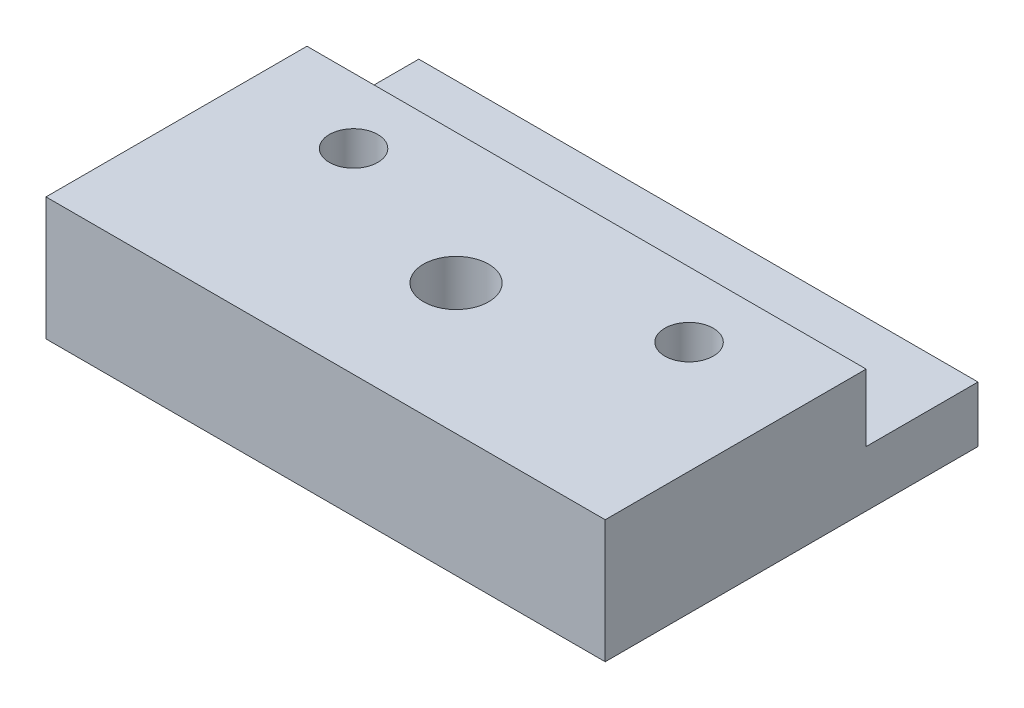
SolidWorks part; units mm, degrees
ref_plane "前基準面" through (0, 0, 0) normal (0, 0, 1) x (1, 0, 0)
ref_plane "上基準面" through (0, 0, 0) normal (0, 1, 0) x (1, 0, 0)
ref_plane "右基準面" through (0, 0, 0) normal (1, 0, 0) x (0, 0, -1)
sketch "草圖1" plane through (0, 0, 0) normal (0, 1, 0) x (1, 0, 0)
  line L1 (0, 0) -> (30, 0)
  line L2 (0, 0) -> (0, 20)
  line L3 (0, 20) -> (30, 20)
  line L4 (30, 0) -> (30, 20)
  dimension "D1" = 20
  dimension "D2" = 30
extrude "填料-伸長1" add sketch "草圖1" along normal blind 3
sketch "草圖2" plane through (0, 3, 0) normal (0, 1, 0) x (1, 0, 0)
  line L0 (30, 0) -> (30, 20) construction
  line L1 (0, 0) -> (30, 0)
  line L2 (0, 0) -> (0, 14)
  line L3 (0, 14) -> (30, 14)
  line L4 (30, 0) -> (30, 14)
  dimension "D1" = 14
extrude "填料-伸長2" add sketch "草圖2" along normal blind 3.6
hole_wizard "Ø2.6 (2.6) 直徑孔1" positions "草圖4" profile "草圖3" hole size "Ø2.6" standard "Ansi Metric" end condition through all
sketch "草圖4" plane through (0, 6.6, 0) normal (0, 1, 0) x (1, 0, 0)
  line L0 (0, 7) -> (30, 7)
  line L1 (0, 14) -> (0, 0) construction
  line L2 (30, 0) -> (30, 14) construction
  line L4 (0, 10.5) -> (30, 10.5)
  line L6 (30, 14) -> (0, 14) construction
  point P0 (6, 10.5)
  point P2 (15, 7)
  point P4 (24, 10.5)
  dimension "D1" = 3.5
  dimension "D2" = 6
  dimension "D3" = 6
sketch "草圖3" plane through (6, 6.6, -10.5) normal (1, 0, 0) x (0, 0, 1)
  line L0 (0, 0) -> (0, 6.6)
  line L1 (0, 6.6) -> (1.3, 6.6)
  line L2 (1.3, 6.6) -> (1.3, 0)
  line L5 (1.3, 0) -> (0, 0)
  line L11 (0, -6.35) -> (0, 107.95) construction
  dimension "貫穿孔直徑" = 2.6
  dimension "貫穿孔深度" = 6.6
hole_wizard "Ø3.5 (3.5) 直徑孔1" positions "草圖6" profile "草圖7" hole size "Ø3.5" standard "Din" end condition through all
sketch "草圖6" plane through (0, 6.6, 0) normal (0, 1, 0) x (1, 0, 0)
  point P0 (15, 7)
sketch "草圖7" plane through (15, 6.6, -7) normal (1, 0, 0) x (0, 0, 1)
  line L0 (0, 0) -> (0, 6.6)
  line L1 (0, 6.6) -> (1.75, 6.6)
  line L2 (1.75, 6.6) -> (1.75, 0)
  line L5 (1.75, 0) -> (0, 0)
  line L11 (0, -6.35) -> (0, 107.95) construction
  dimension "貫穿孔直徑" = 3.5
  dimension "貫穿孔深度" = 6.6
